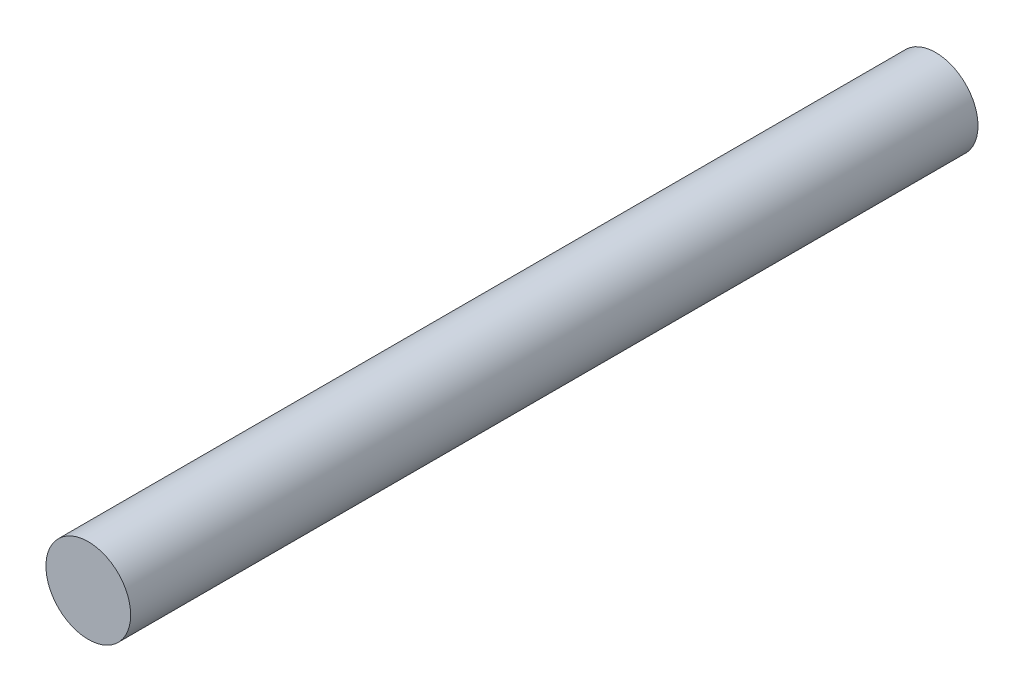
SolidWorks part; units mm, degrees
ref_plane "Přední rovina" through (0, 0, 0) normal (0, 0, 1) x (1, 0, 0)
ref_plane "Horní rovina" through (0, 0, 0) normal (0, 1, 0) x (1, 0, 0)
ref_plane "Pravá rovina" through (0, 0, 0) normal (1, 0, 0) x (0, 0, -1)
sketch "Sketch1" plane through (0, 0, 0) normal (0, 0, 1) x (1, 0, 0)
  circle A0 centre (0, 0) radius 5
  dimension "D1" = 10
extrude "Boss-Extrude1" add sketch "Sketch1" along normal blind 100 contours A0
